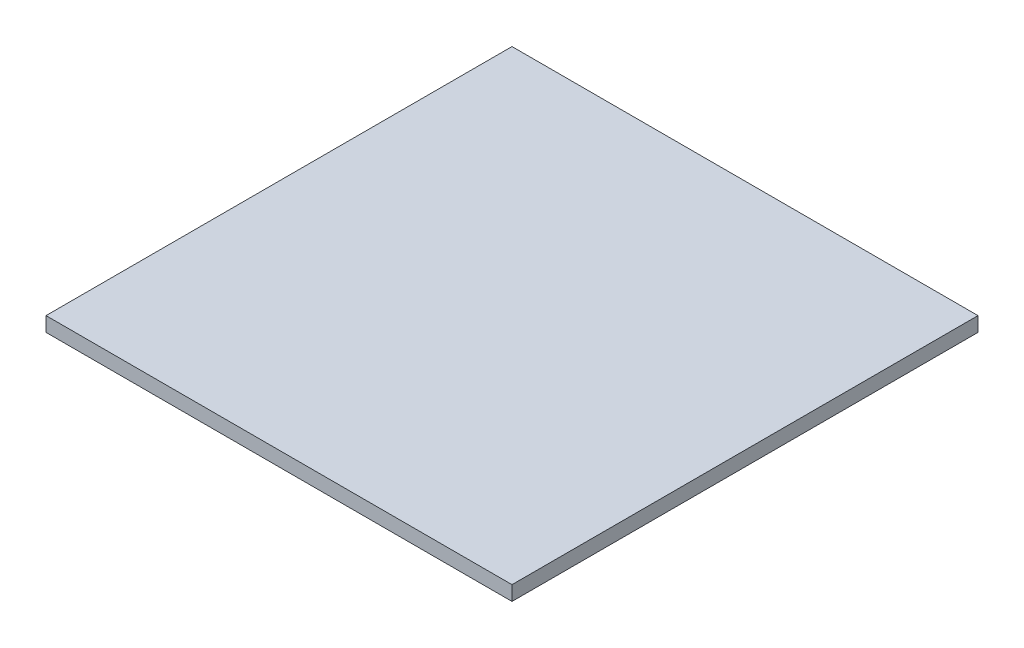
SolidWorks part; units mm, degrees
ref_plane "Front Plane" through (0, 0, 0) normal (0, 0, 1) x (1, 0, 0)
ref_plane "Top Plane" through (0, 0, 0) normal (0, 1, 0) x (1, 0, 0)
ref_plane "Right Plane" through (0, 0, 0) normal (1, 0, 0) x (0, 0, -1)
sketch "Sketch1" plane through (0, 0, 0) normal (0, 1, 0) x (1, 0, 0)
  line L1 (854.075, -850.011) -> (-854.075, -850.011)
  line L2 (854.075, -850.011) -> (854.075, 850.011)
  line L3 (854.075, 850.011) -> (-854.075, 850.011)
  line L4 (-854.075, -850.011) -> (-854.075, 850.011)
  line L5 (854.075, -850.011) -> (-854.075, 850.011) construction
  line L6 (854.075, 850.011) -> (-854.075, -850.011) construction
  point P0 (0, 0)
  dimension "D1" = 1708.15
  dimension "D2" = 1700.022
sketch3d "3DSketch1"
  line L7 (0, 0, -254) -> (0, 0, 0) construction
  line L13 (101.6, 0, -25.4) -> (101.6, 0, -228.6)
  line L14 (101.6, 0, -25.4) -> (-101.6, 0, -25.4)
  line L15 (-101.6, 0, -25.4) -> (-101.6, 0, -228.6)
  line L16 (101.6, 0, -228.6) -> (-101.6, 0, -228.6)
  line L17 (101.6, 0, -25.4) -> (-101.6, 0, -228.6) construction
  line L18 (-101.6, 0, -25.4) -> (101.6, 0, -228.6) construction
  point P9 (0, 0, -127)
  point P12 (0, 0, -127)
  point P14 (0, 0, -127)
  dimension "D1" = 203.2
extrude "Boss-Extrude1" add sketch "3DSketch1" along direction (0, 1, 0) on the side against the normal blind 6.35
